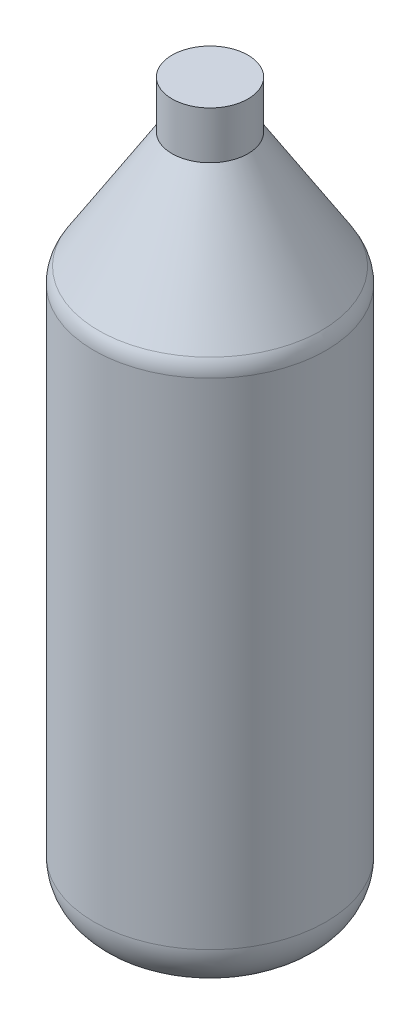
SolidWorks part; units mm, degrees
ref_plane "Front Plane" through (0, 0, 0) normal (0, 0, 1) x (1, 0, 0)
ref_plane "Top Plane" through (0, 0, 0) normal (0, 1, 0) x (1, 0, 0)
ref_plane "Right Plane" through (0, 0, 0) normal (1, 0, 0) x (0, 0, -1)
sketch "Sketch1" plane through (0, 0, 0) normal (0, 1, 0) x (1, 0, 0)
  circle A0 centre (0, 0) radius 30.988
  dimension "D1" = 61.976
extrude "Boss-Extrude1" add sketch "Sketch1" along normal blind 147.32 contours A0
sketch3d "3DSketch1" plane through (0, 0, 0) normal (0, 0, 1) x (1, 0, 0)
  dimension "D1" = 137.16
  dimension "D2" = 180.34
sketch "Sketch3" plane through (0, 180.34, 0) normal (0, -1, 0) x (-1, 0, 0)
  circle A0 centre (0, 0) radius 10.16
loft "Loft2" add profiles "Sketch3" section edge at (0, 147.32, 30.988) section "Sketch3"
fillet "Fillet3" radius 7.62 1 edges at (0, 147.32, 30.988)
sketch "Sketch8" plane through (0, 180.34, 0) normal (0, 1, 0) x (1, 0, 0)
  circle A1 centre (0, 0) radius 10.16
  circle A2 centre (0, 0) radius 10.16
  dimension "D1" = 0
extrude "Boss-Extrude2" add sketch "Sketch8" along normal blind 12.7
fillet "Fillet4" radius 12.7 1 edges at (0, 0, 30.988)
